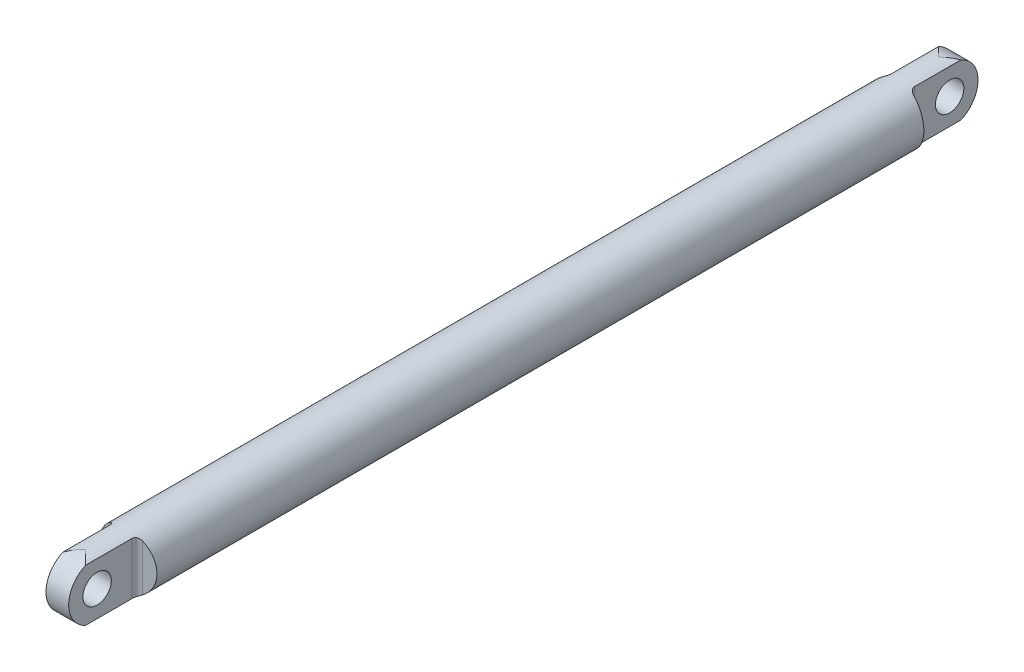
SolidWorks part; units mm, degrees
material "AISI 1045 Steel, cold drawn"
ref_plane "Front Plane" through (0, 0, 0) normal (0, 0, 1) x (1, 0, 0)
ref_plane "Top Plane" through (0, 0, 0) normal (0, 1, 0) x (1, 0, 0)
ref_plane "Right Plane" through (0, 0, 0) normal (1, 0, 0) x (0, 0, -1)
sketch "Sketch1" plane through (0, 0, 0) normal (0, 0, 1) x (1, 0, 0)
  circle A0 centre (0, 0) radius 5
  dimension "D1" = 10
extrude "Boss-Extrude1" add sketch "Sketch1" along normal mid plane 160
sketch "Sketch6" plane through (0, 0, 0) normal (1, 0, 0) x (0, 0, -1)
  line L8 (80, 5) -> (80, -5)
  line L10 (75, -5) -> (80, -5)
  line L13 (80, 5) -> (75, 5)
  line L15 (80, 5) -> (-80, 5) construction
  arc A1 (75, -5) -> (75, 5) centre (75, 0) ccw
  dimension "D1" = 5
extrude "Cut-Extrude2" cut sketch "Sketch6" against normal through all and the other way through all
sketch "Sketch7" plane through (0, 0, 0) normal (0, 1, 0) x (1, 0, 0)
  line L0 (-2, 80) -> (-2, 68)
  line L4 (-5, 80) -> (-5, -80) construction
  line L5 (-5, 67.471) -> (-5, 80)
  line L6 (-5, 80) -> (-2, 80)
  line L7 (0, 3.0864) -> (0, -9.0403) construction
  line L8 (5, 80) -> (2, 80)
  line L9 (2, 80) -> (2, 68)
  line L16 (-5, 67.471) -> (-2, 68)
  line L21 (2, 68) -> (5, 67.471)
  line L22 (5, -80) -> (5, 80) construction
  line L23 (5, 67.471) -> (5, 80)
  dimension "D3" = 100
  dimension "D2" = 12
  dimension "D1" = 2
  dimension "D4" = 100
  dimension "D5" = 2
extrude "Cut-Extrude3" cut sketch "Sketch7" against normal through all both and the other way through all
sketch "Sketch8" plane through (-2, 0, 0) normal (1, 0, 0) x (0, 0, -1)
  circle A0 centre (75, 0) radius 2.5
  arc A7 (77, -4.5826) -> (77, 4.5826) centre (75, 0) ccw construction
  dimension "D1" = 5
extrude "Cut-Extrude4" cut sketch "Sketch8" against normal through all both and the other way through all contours A0
fillet "Fillet1" radius 1 2 edges at (-2, 0, -68) (2, 0, -68)
mirror "Mirror2" about plane through (0, 0, 0) normal (0, 0, 1) of "Cut-Extrude2", "Cut-Extrude3", "Cut-Extrude4", "Fillet1"
equation "\"D4@Sketch7\"=\"D3@Sketch7\""
